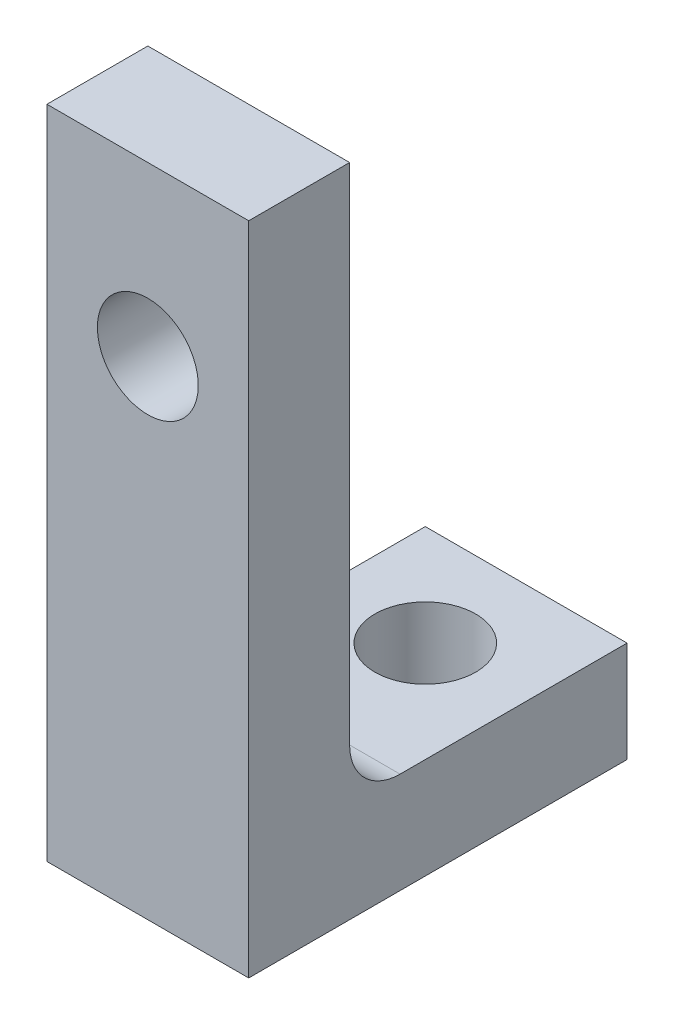
SolidWorks part; units mm, degrees
ref_plane "Front Plane" through (0, 0, 0) normal (0, 0, 1) x (1, 0, 0)
ref_plane "Top Plane" through (0, 0, 0) normal (0, 1, 0) x (1, 0, 0)
ref_plane "Right Plane" through (0, 0, 0) normal (1, 0, 0) x (0, 0, -1)
sketch "Sketch1" plane through (0, 0, 0) normal (1, 0, 0) x (0, 0, -1)
  line L0 (0, 0) -> (0, 11)
  line L1 (0, 11) -> (-2, 11)
  line L2 (-2, 11) -> (-2, -2)
  line L3 (-2, -2) -> (5.5, -2)
  line L4 (5.5, -2) -> (5.5, 0)
  line L5 (5.5, 0) -> (0, 0)
  dimension "D1" = 2
  dimension "D2" = 2
  dimension "D3" = 7.5
  dimension "D4" = 13
extrude "Boss-Extrude1" add sketch "Sketch1" along normal blind 4
sketch "Sketch2" plane through (0, 0, 0) normal (0, 0, -1) x (-1, 0, 0)
  line L0 (-2, 11) -> (-2, -2) construction
  line L1 (-4, 11) -> (0, 11) construction
  line L2 (-4, -2) -> (0, -2) construction
  circle A0 centre (-2, 7.67) radius 1
  dimension "D1" = 2
  dimension "D2" = 9.67
extrude "Cut-Extrude1" cut sketch "Sketch2" against normal through all
sketch "Sketch3" plane through (0, 0, 0) normal (0, 1, 0) x (1, 0, 0)
  line L0 (2, 5.5) -> (2, -2) construction
  line L1 (4, 5.5) -> (0, 5.5) construction
  line L2 (4, -2) -> (0, -2) construction
  circle A0 centre (2, 3.5) radius 1
  dimension "D1" = 2
  dimension "D2" = 5.5
extrude "Cut-Extrude2" cut sketch "Sketch3" against normal through all
fillet "Fillet1" radius 1 1 edges at (2, 0, 0)
